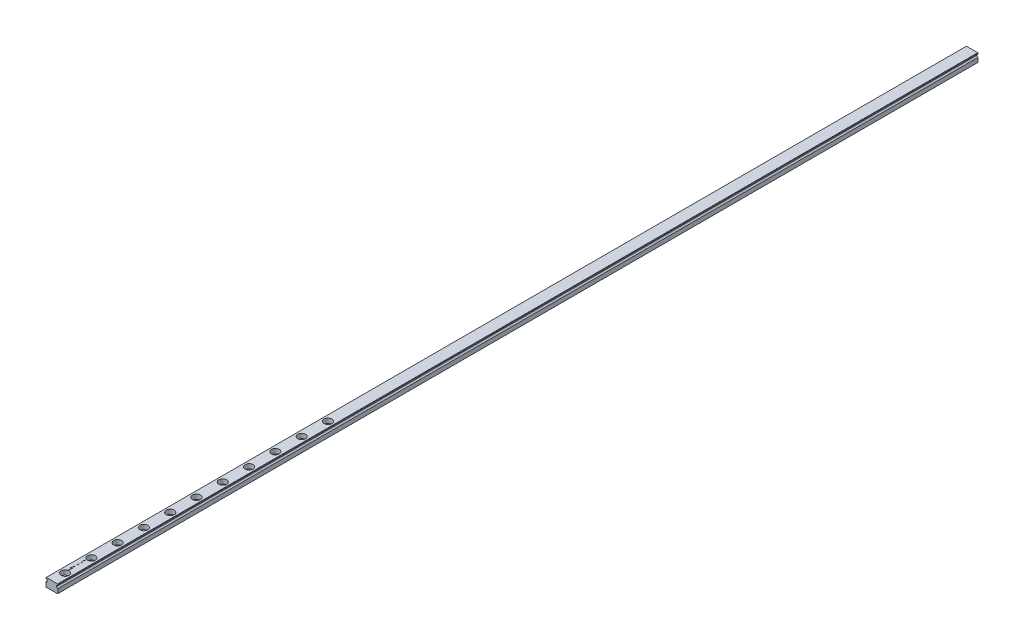
SolidWorks part; units mm, degrees
material "镀铬不锈钢"
ref_plane "前视基准面" through (0, 0, 0) normal (0, 0, 1) x (1, 0, 0)
ref_plane "上视基准面" through (0, 0, 0) normal (0, 1, 0) x (1, 0, 0)
ref_plane "右视基准面" through (0, 0, 0) normal (1, 0, 0) x (0, 0, -1)
sketch "草图1" plane through (0, 0, 0) normal (0, 0, 1) x (1, 0, 0)
  line L2 (4.5, 5.5) -> (4.5, 6.3)
  line L3 (-4.3, 6.5) -> (-4.5, 6.3)
  line L4 (4.5, 0.2) -> (4.5, 3.5)
  line L5 (4.3, 6.5) -> (-4.3, 6.5)
  line L6 (4.5, 6.3) -> (4.3, 6.5)
  line L7 (-4.3, 0) -> (0.2, 0)
  line L8 (4.3, 0) -> (4.5, 0.2)
  line L9 (0.8, 0) -> (4.3, 0)
  line L10 (-4.5, 0.2) -> (-4.3, 0)
  line L11 (0, 6.5) -> (0, 0) construction
  line L12 (-4.5, 3.5) -> (-4.5, 0.2)
  line L13 (-4.5, 6.3) -> (-4.5, 5.5)
  arc A0 (-4.5, 3.5) -> (-4.5, 5.5) centre (-4.5, 4.5) ccw
  arc A1 (0.8, 0) -> (0.2, 0) centre (0.5, 0) ccw
  arc A2 (4.5, 5.5) -> (4.5, 3.5) centre (4.5, 4.5) ccw
extrude "凸台-拉伸1" add sketch "草图1" against normal blind 220
hole_wizard "M3 六角凹头螺钉的柱形沉头孔1" positions "草图3" profile "草图2" counterbore size "M3" standard "ISO" end condition through all
sketch "草图3" plane through (0.7549, 6.5, 19.3435) normal (0, 1, 0) x (-1, 0, 0)
  point P0 (0.7549, -29.3435)
  dimension "D1" = 10
sketch "草图2" plane through (0, 6.5, -10) normal (1, 0, 0) x (0, 0, 1)
  line L0 (0, 0) -> (0, 6.5)
  line L1 (0, 6.5) -> (1.75, 6.5)
  line L3 (1.75, 6.5) -> (1.75, 3.5)
  line L4 (1.75, 3.5) -> (3, 3.5)
  line L5 (3, 3.5) -> (3, 0)
  line L7 (3, 0) -> (0, 0)
  line L11 (0, -6.35) -> (0, 107.95) construction
  dimension "通孔孔直径" = 3.5
  dimension "通孔孔深度" = 6.5
  dimension "柱形沉头孔直径" = 6
  dimension "柱形沉头孔深度" = 3.5
pattern_linear "阵列(线性)1" count 11 spacing 20 along (0, 0, -1) of "M3 六角凹头螺钉的柱形沉头孔1"
sketch "草图6" plane through (0, 6.5, 0) normal (0, 1, 0) x (1, 0, 0)
  line L0 (0, 10) -> (0, 30) construction
  text T0 "HIWIN MGN9" font "Century Gothic" height 1.5
extrude "切除-拉伸1" cut sketch "草图6" against normal blind 0.1
sketch "草图7" plane through (0, 0, -220) normal (0, 0, -1) x (-1, 0, 0)
  line L11 (-4.3, 0) -> (-0.8, 0)
  line L12 (-0.2, 0) -> (4.3, 0)
  line L13 (4.3, 0) -> (4.5, 0.2)
  line L14 (4.5, 0.2) -> (4.5, 3.5)
  line L15 (4.5, 5.5) -> (4.5, 6.3)
  line L16 (4.5, 6.3) -> (4.3, 6.5)
  line L17 (4.3, 6.5) -> (-4.3, 6.5)
  line L18 (-4.3, 6.5) -> (-4.5, 6.3)
  line L19 (-4.5, 6.3) -> (-4.5, 5.5)
  line L20 (-4.5, 3.5) -> (-4.5, 0.2)
  line L21 (-4.5, 0.2) -> (-4.3, 0)
  line L22 (-4.3, 0) -> (-0.8, 0)
  line L23 (-0.2, 0) -> (4.3, 0)
  line L24 (4.3, 0) -> (4.5, 0.2)
  line L25 (4.5, 0.2) -> (4.5, 3.5)
  line L26 (4.5, 5.5) -> (4.5, 6.3)
  line L27 (4.5, 6.3) -> (4.3, 6.5)
  line L28 (4.3, 6.5) -> (-4.3, 6.5)
  line L29 (-4.3, 6.5) -> (-4.5, 6.3)
  line L30 (-4.5, 6.3) -> (-4.5, 5.5)
  line L31 (-4.5, 3.5) -> (-4.5, 0.2)
  line L32 (-4.5, 0.2) -> (-4.3, 0)
  arc A3 (-0.2, 0) -> (-0.8, 0) centre (-0.5, 0) ccw
  arc A4 (4.5, 5.5) -> (4.5, 3.5) centre (4.5, 4.5) ccw
  arc A5 (-4.5, 3.5) -> (-4.5, 5.5) centre (-4.5, 4.5) ccw
  arc A6 (-0.2, 0) -> (-0.8, 0) centre (-0.5, 0) ccw
  arc A7 (4.5, 5.5) -> (4.5, 3.5) centre (4.5, 4.5) ccw
  arc A8 (-4.5, 3.5) -> (-4.5, 5.5) centre (-4.5, 4.5) ccw
  dimension "D1" = 0
extrude "凸台-拉伸2" add sketch "草图7" along normal blind 480
